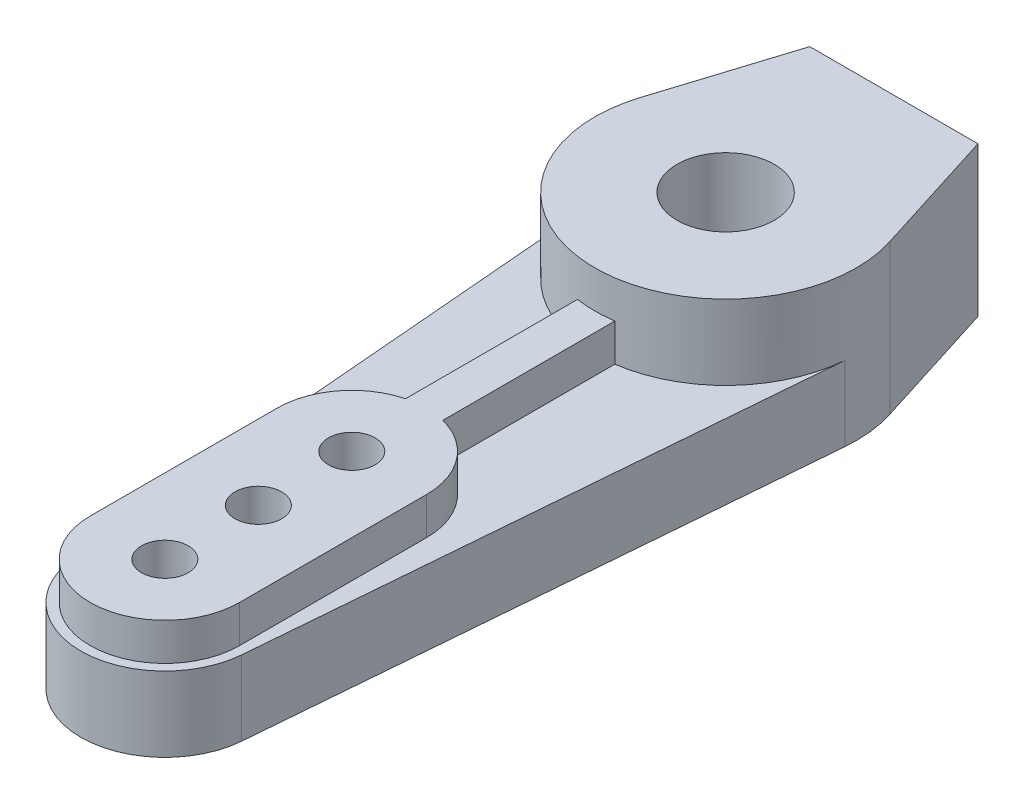
SolidWorks part; units mm, degrees
ref_plane "前视基准面" through (0, 0, 0) normal (0, 0, 1) x (1, 0, 0)
ref_plane "上视基准面" through (0, 0, 0) normal (0, 1, 0) x (1, 0, 0)
ref_plane "右视基准面" through (0, 0, 0) normal (1, 0, 0) x (0, 0, -1)
sketch "草图1" plane through (0, 0, 0) normal (0, 1, 0) x (1, 0, 0)
  line L0 (-4.5, 9) -> (4.5, 9)
  line L1 (-4.5, 9) -> (-6.6755, 2.1067)
  line L2 (4.5, 9) -> (6.6755, 2.1067)
  line L3 (-6.9757, -0.5833) -> (-4.4843, -30.375)
  line L4 (6.9757, -0.5833) -> (4.4843, -30.375)
  arc A0 (-6.6755, 2.1067) -> (6.6755, 2.1067) centre (0, 0) ccw
  circle A1 centre (0, -20) radius 1.25
  circle A2 centre (0, -25) radius 1.25
  circle A3 centre (0, -30) radius 1.25
  circle A4 centre (0, -30) radius 4.5
  point P6 (0, 9)
  dimension "D2" = 14
  dimension "D5" = 5
  dimension "D6" = 5
  dimension "D7" = 2.5
  dimension "D8" = 2.5
  dimension "D9" = 9
  dimension "D1" = 9
  dimension "D3" = 9
  dimension "D4" = 20
extrude "凸台-拉伸1" add sketch "草图1" along normal blind 4 contours A0 L2 L0 L1 | A4 L4 A0 L3 A2 A1 | A4 A2 A3
sketch "草图2" plane through (0, 4, 0) normal (0, 1, 0) x (1, 0, 0)
  line L5 (-6.9757, -0.5833) -> (-4.4843, -30.375)
  line L6 (4.4843, -30.375) -> (6.9757, -0.5833)
  line L7 (6.6755, 2.1067) -> (4.5, 9)
  line L8 (4.5, 9) -> (-4.5, 9)
  line L9 (-4.5, 9) -> (-6.6755, 2.1067)
  line L10 (-6.9757, -0.5833) -> (-4.4843, -30.375)
  line L11 (4.4843, -30.375) -> (6.9757, -0.5833)
  line L12 (6.6755, 2.1067) -> (4.5, 9)
  line L13 (4.5, 9) -> (-4.5, 9)
  line L14 (-4.5, 9) -> (-6.6755, 2.1067)
  circle A0 centre (0, 0) radius 7
  arc A4 (-6.6755, 2.1067) -> (-6.9757, -0.5833) centre (0, 0) ccw
  arc A5 (-4.4843, -30.375) -> (4.4843, -30.375) centre (0, -30) ccw
  arc A6 (6.9757, -0.5833) -> (6.6755, 2.1067) centre (0, 0) ccw
  arc A7 (-6.6755, 2.1067) -> (-6.9757, -0.5833) centre (0, 0) ccw
  arc A8 (-4.4843, -30.375) -> (4.4843, -30.375) centre (0, -30) ccw
  arc A9 (6.9757, -0.5833) -> (6.6755, 2.1067) centre (0, 0) ccw
  arc M10 (-6.6755, 2.1067) -> (-6.9757, -0.5833) centre (0, 0) ccw
  arc M14 (6.9757, -0.5833) -> (6.6755, 2.1067) centre (0, 0) ccw
  line M15 (6.6755, 2.1067) -> (4.5, 9)
  line M16 (4.5, 9) -> (-4.5, 9)
  line M17 (-4.5, 9) -> (-6.6755, 2.1067)
  dimension "D1" = 0
extrude "凸台-拉伸2" add sketch "草图2" along normal blind 4 contours A0 M14 M10 | A0 M15 M16 M17
sketch "草图3" plane through (0, 4, 0) normal (0, 1, 0) x (1, 0, 0)
  line L0 (0, -30) -> (0, -20) construction
  line L1 (-1, -16.9802) -> (1, -16.9802)
  line L2 (-1, -16.9802) -> (-1, -5.9701)
  line L3 (-1, -5.9701) -> (1, -5.9701)
  line L4 (1, -16.9802) -> (1, -5.9701)
  line L5 (-1, -16.9802) -> (1, -5.9701) construction
  line L6 (-1, -5.9701) -> (1, -16.9802) construction
  line L7 (-4, -30) -> (-4, -20)
  line L8 (4, -30) -> (4, -20)
  arc A0 (-4, -30) -> (4, -30) centre (0, -30) ccw
  arc A1 (4, -20) -> (-4, -20) centre (0, -20) ccw
  arc A2 (-4.4843, -30.375) -> (4.4843, -30.375) centre (0, -30) ccw construction
  circle A3 centre (0, -20) radius 1.25 construction
  point P0 (0, -11.4752)
  point P8 (0, -25)
  arc M2 (6.9757, -0.5833) -> (-6.9757, -0.5833) centre (0, 0) cw
  circle M6 centre (0, -25) radius 1.25
  circle M7 centre (0, -20) radius 1.25
  circle M8 centre (0, -30) radius 1.25
  dimension "D1" = 4
  dimension "D2" = 2
extrude "凸台-拉伸3" add sketch "草图3" along normal blind 2 contours L8 A1 L4 L1 L2 L7 A0 M6 M8 M7 | L4 A1 L2 L1 | A1 L4 L2 M2
sketch "草图4" plane through (0, 8, 0) normal (0, 1, 0) x (1, 0, 0)
  circle A0 centre (0, 0) radius 2.6
  dimension "D1" = 5.2
extrude "切除-拉伸1" cut sketch "草图4" against normal blind 6
sketch "草图5" plane through (0, 0, 0) normal (0, -1, 0) x (1, 0, 0)
  circle A0 centre (0, 0) radius 1.5
  dimension "D1" = 3
extrude "切除-拉伸2" cut sketch "草图5" against normal through all
